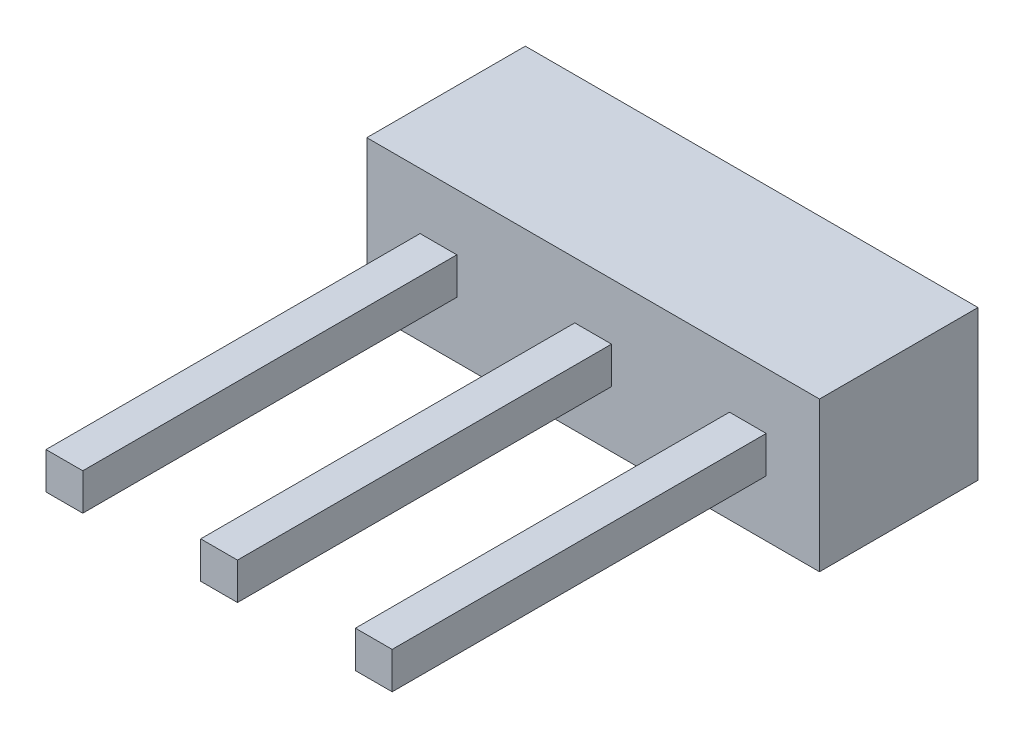
SolidWorks part; units mm, degrees
ref_plane "Přední rovina" through (0, 0, 0) normal (0, 0, 1) x (1, 0, 0)
ref_plane "Horní rovina" through (0, 0, 0) normal (0, 1, 0) x (1, 0, 0)
ref_plane "Pravá rovina" through (0, 0, 0) normal (1, 0, 0) x (0, 0, -1)
sketch "Skica1" plane through (0, 0, 0) normal (0, 0, 1) x (1, 0, 0)
  line L1 (-3.57, -1.18) -> (3.57, -1.18)
  line L2 (-3.57, -1.18) -> (-3.57, 1.18)
  line L3 (-3.57, 1.18) -> (3.57, 1.18)
  line L4 (3.57, -1.18) -> (3.57, 1.18)
  line L5 (-3.57, -1.18) -> (3.57, 1.18) construction
  line L6 (-3.57, 1.18) -> (3.57, -1.18) construction
  point P0 (0, 0)
  dimension "D1" = 7.14
  dimension "D2" = 2.36
extrude "Přidat vysunutím1" add sketch "Skica1" along normal blind 2.5
sketch "Skica2" plane through (0, 0, 2.5) normal (0, 0, 1) x (1, 0, 0)
  line L0 (3.57, -1.18) -> (3.57, 1.18) construction
  line L1 (2.73, 0.29) -> (2.15, 0.29)
  line L2 (2.73, 0.29) -> (2.73, -0.29)
  line L3 (2.73, -0.29) -> (2.15, -0.29)
  line L4 (2.15, 0.29) -> (2.15, -0.29)
  line L5 (2.73, 0.29) -> (2.15, -0.29) construction
  line L6 (2.73, -0.29) -> (2.15, 0.29) construction
  line L7 (-3.57, 0) -> (3.57, 0) construction
  line L8 (-3.57, 1.18) -> (-3.57, -1.18) construction
  point P0 (2.44, 0)
  dimension "D1" = 0.84
  dimension "D2" = 0.58
extrude "Přidat vysunutím2" add sketch "Skica2" along normal blind 5.9
pattern_linear "LinPole1" count 3 spacing 2.44 along (-1, 0, 0) of "Přidat vysunutím2"
